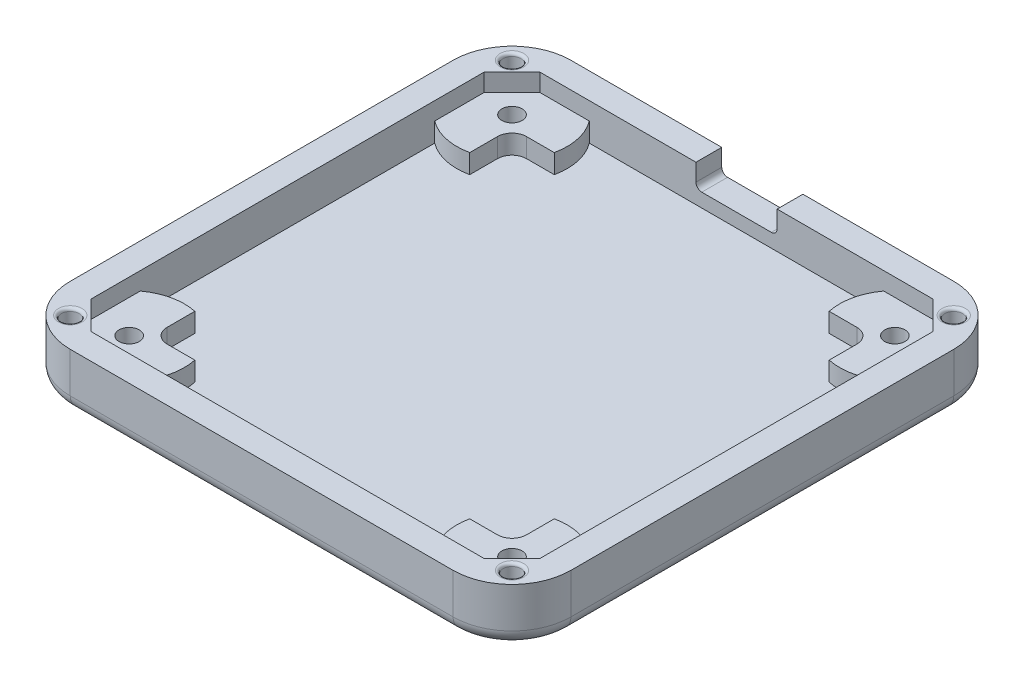
SolidWorks part; units mm, degrees
ref_plane "Front Plane" through (0, 0, 0) normal (0, 0, 1) x (1, 0, 0)
ref_plane "Top Plane" through (0, 0, 0) normal (0, 1, 0) x (1, 0, 0)
ref_plane "Right Plane" through (0, 0, 0) normal (1, 0, 0) x (0, 0, -1)
sketch "Sketch1" plane through (0, 0, 0) normal (0, 1, 0) x (1, 0, 0)
  line L1 (-33.02, 43.18) -> (33.02, 43.18)
  line L2 (-43.18, 33.02) -> (-43.18, -33.02)
  line L3 (-33.02, -43.18) -> (33.02, -43.18)
  line L4 (43.18, 33.02) -> (43.18, -33.02)
  line L5 (-43.18, 43.18) -> (43.18, -43.18) construction
  line L6 (-43.18, -43.18) -> (43.18, 43.18) construction
  arc A0 (-43.18, -33.02) -> (-33.02, -43.18) centre (-33.02, -33.02) ccw
  arc A1 (33.02, -43.18) -> (43.18, -33.02) centre (33.02, -33.02) ccw
  arc A2 (33.02, 43.18) -> (43.18, 33.02) centre (33.02, 33.02) cw
  arc A3 (-33.02, 43.18) -> (-43.18, 33.02) centre (-33.02, 33.02) ccw
  point P0 (0, 0)
  dimension "D3" = 10.16
  dimension "D1" = 86.36
  dimension "D2" = 86.36
extrude "Boss-Extrude1" add sketch "Sketch1" along normal blind 24.9936
sketch "Sketch2" plane through (0, 0, -43.18) normal (0, 0, -1) x (-1, 0, 0)
  line L0 (-33.02, 8.0264) -> (33.02, 8.0264) construction
  line L1 (-33.02, 24.9936) -> (-33.02, 0) construction
  line L2 (33.02, 24.9936) -> (33.02, 0) construction
  line L3 (-33.02, 24.9936) -> (33.02, 24.9936) construction
  line L4 (-33.02, 6.4516) -> (33.02, 6.4516) construction
  line L5 (-7, 8.0264) -> (-7, 5.5264)
  line L6 (-7, 5.5264) -> (7, 5.5264)
  line L7 (-7, 8.0264) -> (-7, 12.5264)
  line L8 (-7, 12.5264) -> (7, 12.5264)
  line L9 (7, 8.0264) -> (7, 12.5264)
  line L10 (7, 5.5264) -> (7, 8.0264)
  dimension "D1" = 16.9672
  dimension "D2" = 1.5748
  dimension "D3" = 7
  dimension "D4" = 7
  dimension "D5" = 4.5
  dimension "D6" = 2.5
extrude "Cut-Extrude1" cut sketch "Sketch2" against normal blind 20
sketch "Sketch5" plane through (0, 0, -43.18) normal (0, 0, -1) x (-1, 0, 0)
  line L1 (-46.3694, 29.4023) -> (46.3694, 29.4023)
  line L2 (-46.3694, 29.4023) -> (-46.3694, 9.5021)
  line L3 (-46.3694, 9.5021) -> (46.3694, 9.5021)
  line L4 (46.3694, 29.4023) -> (46.3694, 9.5021)
  line L5 (-46.3694, 29.4023) -> (46.3694, 9.5021) construction
  line L6 (-46.3694, 9.5021) -> (46.3694, 29.4023) construction
  point P0 (0, 19.4522)
extrude "Cut-Extrude2" cut sketch "Sketch5" against normal blind 127
sketch "Sketch7" plane through (0, 9.5021, 0) normal (0, 1, 0) x (1, 0, 0)
  line L0 (-38.735, 33.909) -> (-33.909, 38.735)
  line L1 (-33.909, 38.735) -> (33.909, 38.735)
  line L2 (-38.735, 33.909) -> (-38.735, -33.909)
  line L3 (-33.909, -38.735) -> (33.909, -38.735)
  line L4 (38.735, 33.909) -> (38.735, -33.909)
  line L5 (-38.735, 38.735) -> (38.735, -38.735) construction
  line L6 (-38.735, -38.735) -> (38.735, 38.735) construction
  line L7 (33.909, 38.735) -> (38.735, 33.909)
  line L8 (33.909, -38.735) -> (38.735, -33.909)
  line L9 (-38.735, -33.909) -> (-33.909, -38.735)
  point P0 (0, 0)
  dimension "D1" = 77.47
  dimension "D2" = 77.47
  dimension "D5" = 4.826
  dimension "D6" = 4.826
  dimension "D7" = 4.826
  dimension "D8" = 4.826
extrude "Cut-Extrude3" cut sketch "Sketch7" against normal blind 6.35
sketch "Sketch8" plane through (0, 3.1521, 0) normal (0, 1, 0) x (1, 0, 0)
  line L0 (33.909, 38.735) -> (-33.909, 38.735) construction
  line L1 (-38.735, 33.909) -> (-38.735, -33.909) construction
  line L6 (0, 38.735) -> (0, -38.735) construction
  line L7 (-33.909, -38.735) -> (33.909, -38.735) construction
  line L8 (-38.735, 0) -> (38.735, 0) construction
  line L9 (-38.735, 33.909) -> (-38.735, -33.909) construction
  line L10 (38.735, -33.909) -> (38.735, 33.909) construction
  circle A0 centre (-33.02, 33.02) radius 9.525
  circle A1 centre (33.02, 33.02) radius 9.525
  circle A2 centre (-33.02, -33.02) radius 9.525
  circle A3 centre (33.02, -33.02) radius 9.525
  dimension "D1" = 19.05
  dimension "D3" = 5.715
  dimension "D4" = 5.715
extrude "Boss-Extrude2" add sketch "Sketch8" along normal blind 3.302
fillet "Fillet2" radius 2.54 8 edges at (0, 0, 43.18) (40.2042, 0, 40.2042) (43.18, 0, 0) (40.2042, 0, -40.2042) (0, 0, -43.18) (-40.2042, 0, -40.2042) (-43.18, 0, 0) (-40.2042, 0, 40.2042)
sketch "Sketch9" plane through (0, 6.4541, 0) normal (0, 1, 0) x (1, 0, 0)
  line L1 (0, 38.735) -> (0, -38.735) construction
  line L3 (-33.909, -38.735) -> (33.909, -38.735) construction
  line L4 (-38.735, 0) -> (38.735, 0) construction
  line L5 (-38.735, 25.4) -> (-38.735, -25.4) construction
  line L6 (38.735, -33.909) -> (38.735, 33.909) construction
  circle A0 centre (-33.02, 33.02) radius 1.7488
  circle A1 centre (33.02, 33.02) radius 1.7488
  circle A2 centre (-33.02, -33.02) radius 1.7488
  circle A3 centre (33.02, -33.02) radius 1.7488
  dimension "D1" = 3.4976
extrude "Cut-Extrude4" cut sketch "Sketch9" against normal blind 15.6972
sketch "Sketch10" plane through (0, 0, 0) normal (0, -1, 0) x (1, 0, 0)
  circle A0 centre (-33.02, -33.02) radius 3.25
  circle A1 centre (-33.02, 33.02) radius 3.25
  circle A2 centre (33.02, 33.02) radius 3.25
  circle A3 centre (33.02, -33.02) radius 3.25
  dimension "D1" = 6.5
  dimension "D2" = 6.5
  dimension "D3" = 6.5
  dimension "D4" = 6.5
extrude "Cut-Extrude5" cut sketch "Sketch10" against normal blind 4
sketch "Sketch11" plane through (0, 9.5021, 0) normal (0, 1, 0) x (1, 0, 0)
  line L0 (-7, 43.18) -> (-33.02, 43.18) construction
  line L1 (-43.18, -33.02) -> (-43.18, 33.02) construction
  circle A0 centre (-38.1, 38.1) radius 1.524
  dimension "D3" = 3.048
  dimension "D1" = 5.08
  dimension "D2" = 5.08
extrude "Cut-Extrude6" cut sketch "Sketch11" against normal blind 5.08
mirror "Mirror1" about plane through (0, 0, 0) normal (1, 0, 0) of "Cut-Extrude6"
mirror "Mirror2" about plane through (0, 0, 0) normal (0, 0, 1) of "Mirror1", "Cut-Extrude6"
fillet "Fillet3" radius 0.508 4 edges at (-38.1, 9.5021, 36.576) (38.1, 9.5021, 36.576) (38.1, 9.5021, -36.576) (-38.1, 9.5021, -36.576)
sketch "Sketch12" plane through (0, 6.4541, 0) normal (0, 1, 0) x (1, 0, 0)
  line L1 (28.5, -31) -> (-28.5, -31)
  line L2 (31, -28.5) -> (31, 28.5)
  line L3 (28.5, 31) -> (-28.5, 31)
  line L4 (-31, -28.5) -> (-31, 28.5)
  line L5 (31, -31) -> (-31, 31) construction
  line L6 (31, 31) -> (-31, -31) construction
  arc A0 (31, 28.5) -> (28.5, 31) centre (28.5, 28.5) ccw
  arc A1 (-28.5, 31) -> (-31, 28.5) centre (-28.5, 28.5) ccw
  arc A2 (-28.5, -31) -> (-31, -28.5) centre (-28.5, -28.5) cw
  arc A3 (28.5, -31) -> (31, -28.5) centre (28.5, -28.5) ccw
  point P0 (0, 0)
  dimension "D3" = 2.5
  dimension "D1" = 62
  dimension "D2" = 62
extrude "Cut-Extrude7" cut sketch "Sketch12" against normal up to surface (3.302 mm away) up to face at (0, 3.1521, 0)
fillet "Fillet5" radius 1 2 edges at (7, 5.5264, -40.9575) (-7, 5.5264, -40.9575)
